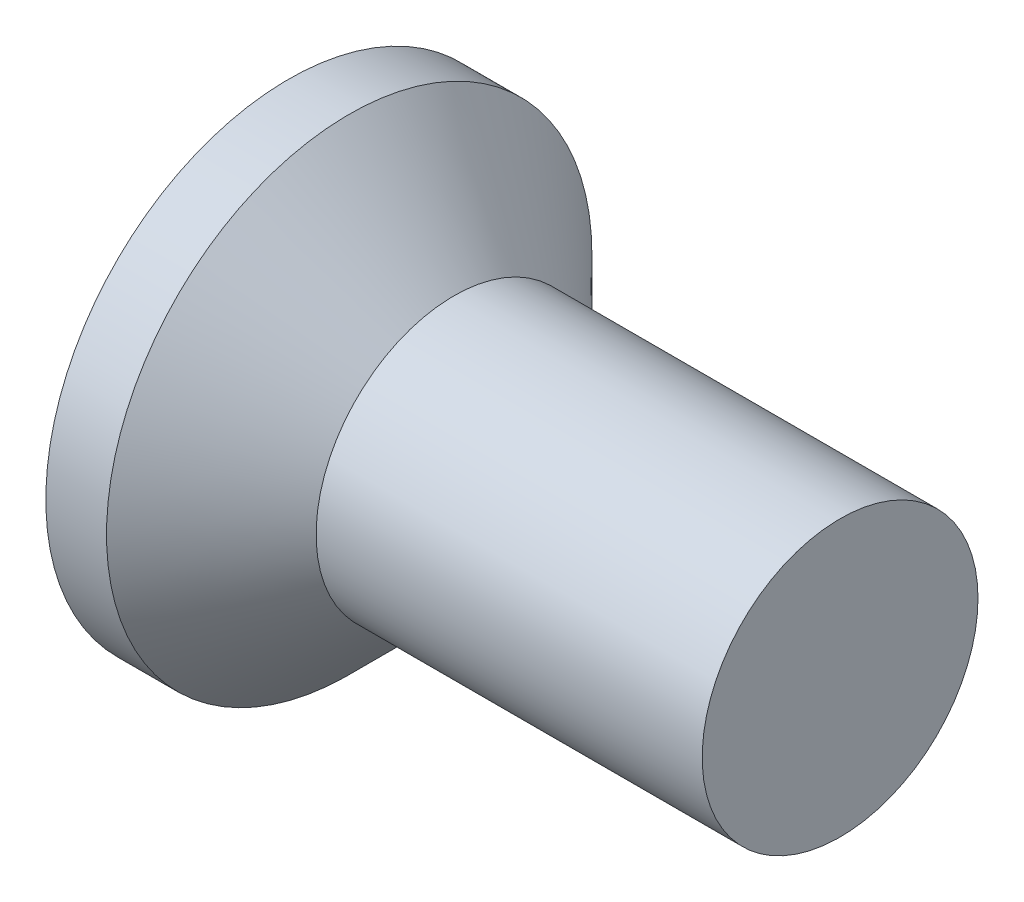
SolidWorks part; units mm, degrees
ref_plane "Front" through (0, 0, 0) normal (0, 0, 1) x (1, 0, 0)
ref_plane "Top" through (0, 0, 0) normal (0, 1, 0) x (1, 0, 0)
ref_plane "Right" through (0, 0, 0) normal (1, 0, 0) x (0, 0, -1)
sketch "Sketch1" plane through (0, 0, 0) normal (0, 0, 1) x (1, 0, 0)
  line L0 (5, 1.25) -> (2.4, 1.25)
  line L1 (2.4, 1.25) -> (1.5, 1.25)
  line L2 (1.5, 1.25) -> (0.55, 2.2)
  line L3 (0.55, 2.2) -> (0, 2.2)
  line L4 (5, 1.25) -> (5, 0)
  line L5 (4.5158, 0) -> (-89.8219, 0) construction
  line L6 (5, 0) -> (0, 0)
  line L7 (0, 2.2) -> (0, 0)
  dimension "D1" = 45
  dimension "dk" = 4.4
  dimension "l" = 5
  dimension "k" = 1.5
  dimension "a" = 0.9
  dimension "d" = 2.5
revolve "Base" add sketch "Sketch1" angle 360 about L5
cosmetic thread "ThreadCosmetic1" [suppressed] parameters "bb"=3.5
sketch "Sketch6" plane through (0, 0, 0) normal (1, 0, 0) x (0, 0, -1)
  line L0 (-1.9271, 0) -> (2.0512, 0) construction
  line L1 (0, 1.8651) -> (0, -2.0207) construction
  line L2 (0.29, 0.29) -> (0.29, 1.45)
  line L3 (0.29, 1.45) -> (-0.29, 1.45)
  line L4 (-0.29, 0.29) -> (-0.29, 1.45)
  line L5 (0.29, 0.29) -> (1.45, 0.29)
  line L6 (1.45, 0.29) -> (1.45, -0.29)
  line L7 (-1.45, 0.29) -> (-1.45, -0.29)
  line L8 (-0.29, 0.29) -> (-1.45, 0.29)
  line L9 (-0.29, -0.29) -> (-1.45, -0.29)
  line L10 (0.29, -0.29) -> (1.45, -0.29)
  line L11 (-0.29, -0.29) -> (-0.29, -1.45)
  line L12 (0.29, -1.45) -> (-0.29, -1.45)
  line L13 (0.29, -0.29) -> (0.29, -1.45)
  point P16 (-1.45, 0)
  point P17 (1.45, 0)
extrude "CrossRecess" cut sketch "Sketch6" along normal blind 0.75
draft "Draft9" type of draft neutral plane draft angle 30 faces to draft 4 face at (0.375, -1.45, 0) face at (0.375, 0, 1.45) face at (0.375, 0, -1.45) face at (0.375, 1.45, 0) neutral plane through (0, 2.2, 0) neutral plane normal (-1, 0, 0) parameters "D1"=30
fillet "Fillet5" radius 0.3 4 edges at (0.375, -0.29, -0.29) (0.375, -0.29, 0.29) (0.375, 0.29, -0.29) (0.375, 0.29, 0.29)
sketch "Sketch7" plane through (0, 0, 0) normal (1, 0, 0) x (0, 0, -1)
  line L0 (-2.0126, 0) -> (1.9757, 0) construction
  line L1 (0, 1.9314) -> (0, -2.0126) construction
  line L2 (0, 0) -> (1.5555, 1.5555) construction
  line L3 (0, 0.4333) -> (1.0253, 1.0253)
  line L4 (-1.5402, 1.5402) -> (0, 0) construction
  line L5 (0.4333, 0) -> (1.0253, 1.0253)
  line L6 (0, -0.4333) -> (1.0253, -1.0253)
  line L7 (0.4333, 0) -> (1.0253, -1.0253)
  line L8 (-0.4333, 0) -> (-1.0253, -1.0253)
  line L9 (0, -0.4333) -> (-1.0253, -1.0253)
  line L10 (-0.4333, 0) -> (-1.0253, 1.0253)
  line L11 (0, 0.4333) -> (-1.0253, 1.0253)
  dimension "D3" = 15
  dimension "m" = 2.9
extrude "Cut-Extrude3" [suppressed] cut sketch "Sketch7" along normal blind 10 draft 20
sketch "Sketch10" plane through (0, 0, 0) normal (0, 0, 1) x (1, 0, 0)
  line L0 (62.2289, 0) -> (-1.9277, 0) construction
  line L1 (1.5, 1.25) -> (1.95, 1.25)
  line L4 (1.95, 1.25) -> (1.95, 0)
  line L7 (1.95, 0) -> (1.5, 0)
  line L9 (1.5, 1.25) -> (0.55, 2.2) construction
  line L10 (1.5, 1.25) -> (1.5, 0)
  dimension "p" = 0.45
revolve "Revolve2" add sketch "Sketch10" angle 360 about L0
sketch "Sketch8" plane through (0, 0, 0) normal (0, 0, 1) x (1, 0, 0)
  line L0 (-20, 1.25) -> (-21.1, 1.0065)
  line L1 (-21.1, 1.0065) -> (5, 1.0065)
  line L3 (5, -1.25) -> (5, 1.25) construction
  line L6 (5, 1.0065) -> (5, 6.0065)
  line L7 (5, 6.0065) -> (-20, 6.0065)
  line L8 (-20, 6.0065) -> (-20, 1.25)
  line L9 (62.4753, 0) -> (52.9594, 0) construction
  dimension "D1" = 5
  dimension "x" = 1.1
  dimension "d" = 2.5
  dimension "THD_MINOR" = 2.013
  dimension "b" = 25
sketch "Sketch11" plane through (0, 0, 0) normal (0, 0, 1) x (1, 0, 0)
  line L0 (5, 1.0391) -> (5.1217, 1.25)
  line L1 (5.1217, 1.25) -> (5.1217, 1.4935)
  line L2 (5.1217, 1.4935) -> (4.8782, 1.4935)
  line L3 (4.8782, 1.4935) -> (4.8782, 1.25)
  line L4 (4.8782, 1.25) -> (5, 1.0391)
  line L5 (5, -1.25) -> (5, 1.25) construction
  line L6 (0, 0) -> (66.0064, 0) construction
  dimension "D1" = 2.5
  dimension "D2" = 0.2435
revolve "Cut-Revolve10" [suppressed] cut sketch "Sketch11" angle 360 about L6
pattern_linear "LPattern10" [suppressed] count 12 spacing 0.2922 along (1, 0, 0)
equation "\"D1@Sketch6\" = \"m@Sketch6\" / 5"
equation "\"D1@CrossRecess\" = \"k@Sketch1\" / 2"
equation "\"D1@Sketch11\" = \"d@Sketch1\""
equation "\"D2@Sketch11\" =  ( \"d@Sketch1\" - \"THD_MINOR@ThreadCosmetic1\" )  / 2"
equation "\"D3@LPattern10\" = \"D2@Sketch11\" * 1.2"
equation "\"D1@LPattern10\" = \"bb@ThreadCosmetic1\" / \"D3@LPattern10\" "
